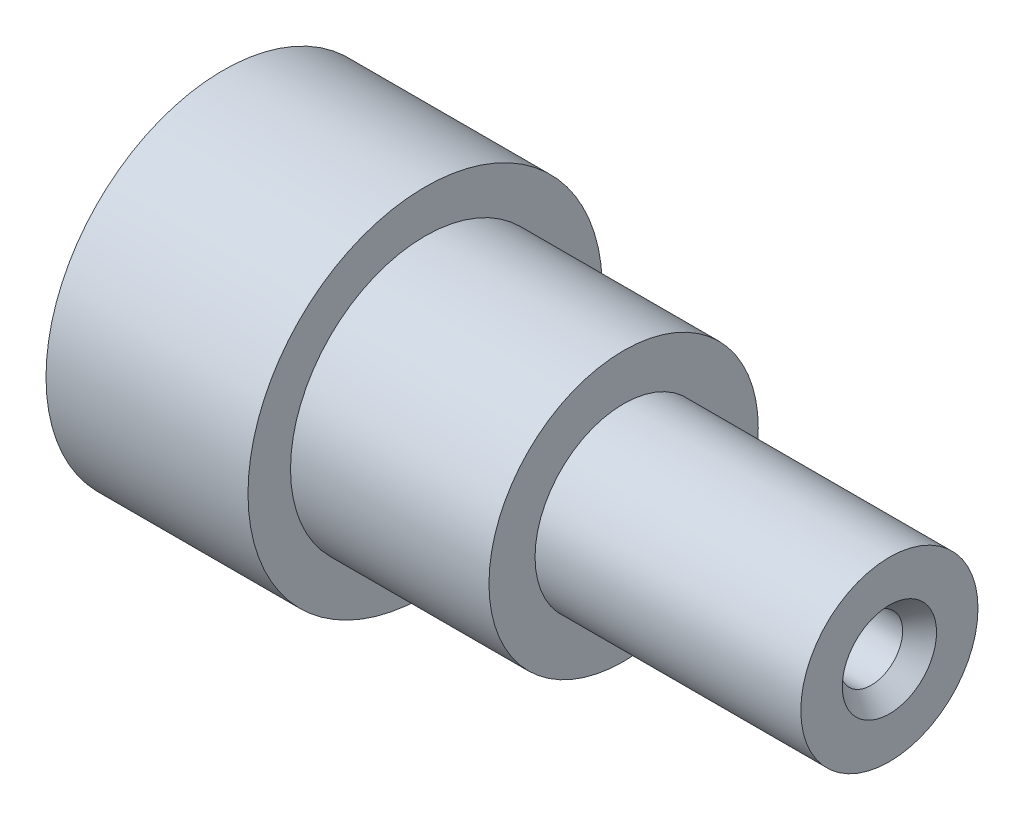
SolidWorks part; units mm, degrees
ref_plane "Front Plane" through (0, 0, 0) normal (0, 0, 1) x (1, 0, 0)
ref_plane "Top Plane" through (0, 0, 0) normal (0, 1, 0) x (1, 0, 0)
ref_plane "Right Plane" through (0, 0, 0) normal (1, 0, 0) x (0, 0, -1)
sketch "Sketch3" plane through (0, 0, 0) normal (0, 1, 0) x (1, 0, 0)
  line L0 (-22.6005, 0) -> (25.1515, 0)
  line L1 (25.1515, 0) -> (25.1515, 6.35)
  line L2 (25.1515, 6.35) -> (6.1015, 6.35)
  line L3 (6.1015, 6.35) -> (6.1015, 9.652)
  line L4 (6.1015, 9.652) -> (-8.1225, 9.652)
  line L5 (-8.1225, 9.652) -> (-8.1225, 12.7)
  line L6 (-8.1225, 12.7) -> (-22.6005, 12.7)
  line L7 (-22.6005, 12.7) -> (-22.6005, 0)
  dimension "D1" = 47.752
  dimension "D2" = 6.35
  dimension "D3" = 9.652
  dimension "D4" = 12.7
  dimension "D5" = 33.274
  dimension "D6" = 19.05
revolve "Revolve1" add sketch "Sketch3" angle 360 about L0
hole_wizard "#12-24 Tapped Hole1" positions "Sketch8" profile "Sketch9" tap size "#12-24" standard "ANSI Inch"
sketch "Sketch8" plane through (25.1515, 0, 0) normal (1, 0, 0) x (0, 0, -1)
  point P1 (0, 0)
sketch "Sketch9" plane through (25.1515, 0, 0) normal (0, 1, 0) x (0, 0, -1)
  line L0 (0, 0) -> (0, 20.4007)
  line L1 (0, 20.4007) -> (2.2479, 19.05)
  line L2 (2.2479, 19.05) -> (2.2479, 1.3003)
  line L3 (2.2479, 1.3003) -> (3.3782, 0)
  line L5 (3.3782, 0) -> (0, 0)
  line L6 (-2.2479, 1.3003) -> (-3.3782, 0) construction
  line L10 (0, 20.4007) -> (-2.2479, 19.05) construction
  line L11 (0, -6.35) -> (0, 107.95) construction
  dimension "Tap Drill Dia." = 4.4958
  dimension "Tap Drill Depth" = 19.05
  dimension "Near C'Sink Dia." = 6.7564
  dimension "Near C'Sink Angle" = 82
  dimension "Drill Angle" = 118
cosmetic thread "Hole Thread2" parameters "D1"=10.922, "D2"=5.4864
